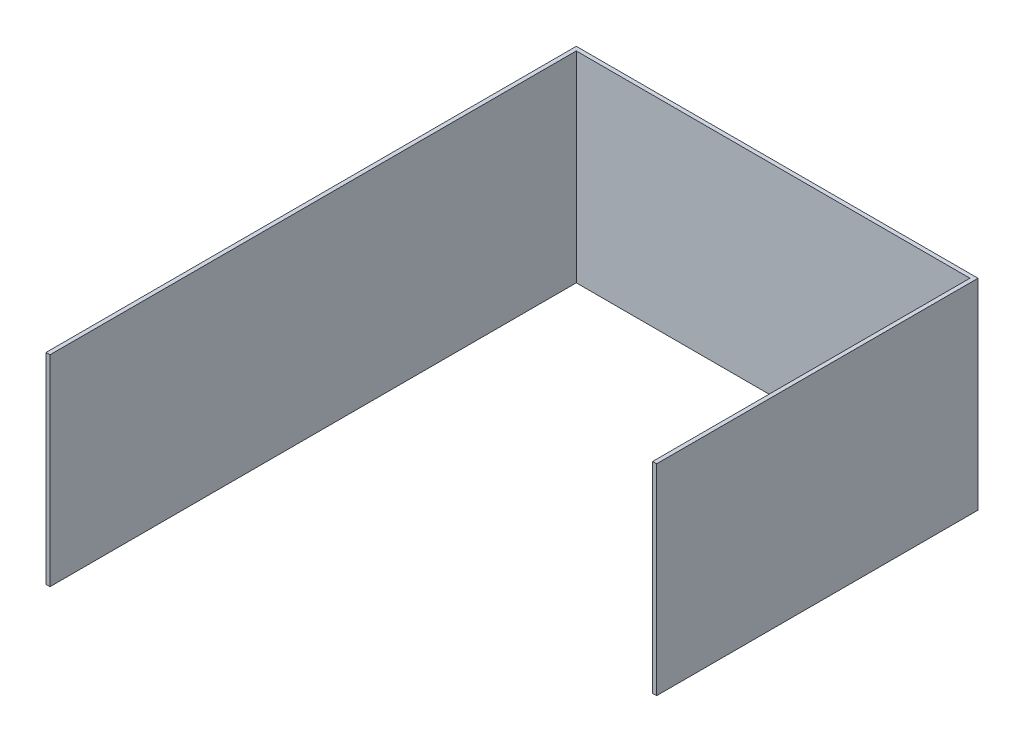
SolidWorks part; units mm, degrees
ref_plane "Front Plane" through (0, 0, 0) normal (0, 0, 1) x (1, 0, 0)
ref_plane "Top Plane" through (0, 0, 0) normal (0, 1, 0) x (1, 0, 0)
ref_plane "Right Plane" through (0, 0, 0) normal (1, 0, 0) x (0, 0, -1)
sketch "Sketch1" plane through (0, 0, 0) normal (0, 1, 0) x (1, 0, 0)
  line L0 (-250, 0) -> (-250, 500)
  line L1 (-250, 500) -> (250, 500)
  line L2 (250, 500) -> (250, 0)
  line L3 (250, 0) -> (245, 0)
  line L4 (245, 0) -> (245, 495)
  line L5 (245, 495) -> (-245, 495)
  line L6 (-245, 495) -> (-245, 0)
  line L7 (-245, 0) -> (-250, 0)
  dimension "D1" = 5
  dimension "D2" = 5
  dimension "D3" = 5
  dimension "D4" = 250
  dimension "D5" = 250
  dimension "D6" = 500
extrude "Boss-Extrude1" add sketch "Sketch1" along normal blind 250
sketch "Sketch3" plane through (0, 250, 0) normal (0, 1, 0) x (1, 0, 0)
  line L0 (250, 0) -> (250, 500) construction
  line L1 (245, 0) -> (250, 0)
  line L2 (245, 0) -> (245, 100)
  line L3 (245, 100) -> (250, 100)
  line L4 (250, 0) -> (250, 100)
  dimension "D1" = 100
extrude "Cut-Extrude1" cut sketch "Sketch3" against normal blind 250
sketch "Sketch4" plane through (0, 0, 0) normal (0, 0, 1) x (1, 0, 0)
  line L0 (-245, 0) -> (245, 0) construction
  line L1 (-250, 250) -> (-245, 250)
  line L2 (-250, 250) -> (-250, 0)
  line L3 (-250, 0) -> (-245, 0)
  line L4 (-245, 250) -> (-245, 0)
  line L5 (-245, 250) -> (-245, 0) construction
extrude "Boss-Extrude2" add sketch "Sketch4" along normal blind 160
